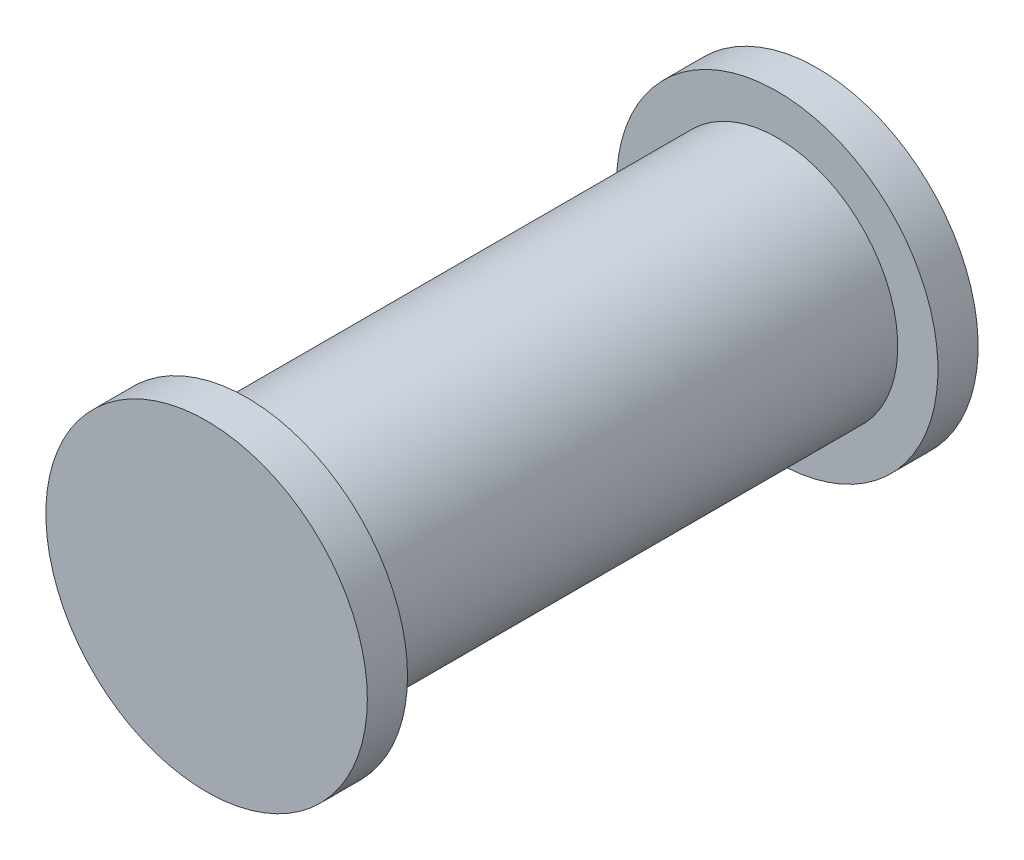
SolidWorks part; units mm, degrees
ref_plane "前视基准面" through (0, 0, 0) normal (0, 0, 1) x (1, 0, 0)
ref_plane "上视基准面" through (0, 0, 0) normal (0, 1, 0) x (1, 0, 0)
ref_plane "右视基准面" through (0, 0, 0) normal (1, 0, 0) x (0, 0, -1)
sketch "草图1" plane through (0, 0, 0) normal (0, 0, 1) x (1, 0, 0)
  circle A0 centre (0, 0) radius 30
extrude "凸台-拉伸1" add sketch "草图1" along normal blind 132
sketch "草图2" plane through (0, 0, 132) normal (0, 0, 1) x (1, 0, 0)
  circle A0 centre (0, 0) radius 40
extrude "凸台-拉伸2" add sketch "草图2" along normal blind 10
sketch "草图3" plane through (0, 0, 0) normal (0, 0, -1) x (-1, 0, 0)
  circle A0 centre (0, 0) radius 40
extrude "凸台-拉伸3" add sketch "草图3" along normal blind 10
scale "缩放比例1" scale about origin uniform scaling yes scale factor 0.345
